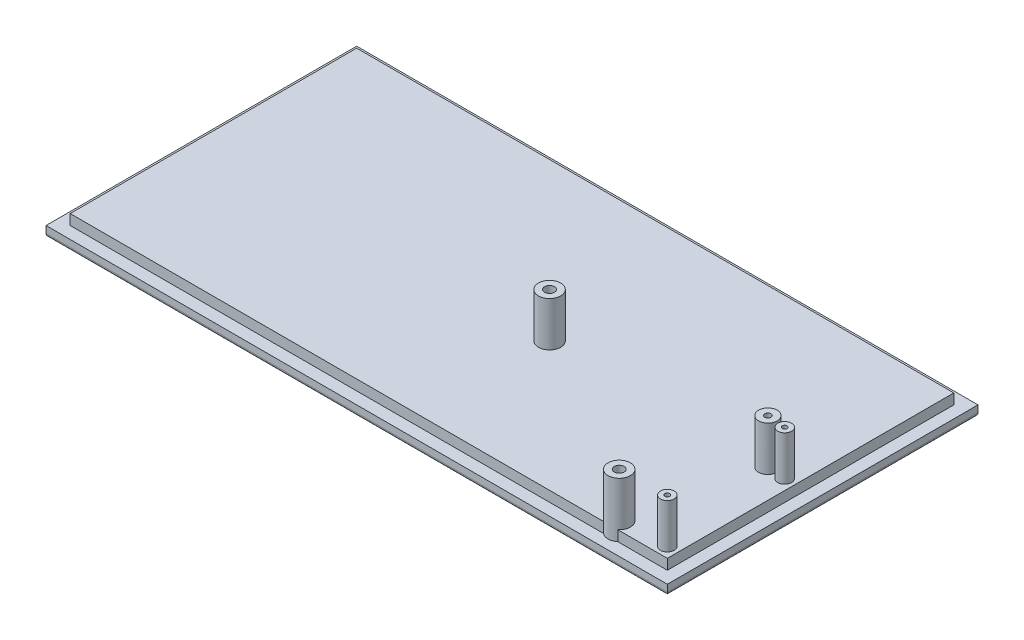
SolidWorks part; units mm, degrees
ref_plane "前视基准面" through (0, 0, 0) normal (0, 0, 1) x (1, 0, 0)
ref_plane "上视基准面" through (0, 0, 0) normal (0, 1, 0) x (1, 0, 0)
ref_plane "右视基准面" through (0, 0, 0) normal (1, 0, 0) x (0, 0, -1)
other "Configuration Table"
sketch "草图1" plane through (0, 0, 0) normal (0, 1, 0) x (1, 0, 0)
  line L1 (-90, 45) -> (90, 45)
  line L2 (-90, 45) -> (-90, -45)
  line L3 (-90, -45) -> (90, -45)
  line L4 (90, 45) -> (90, -45)
  point P7 (25.1581, 37.3018)
  dimension "D1" = 90
  dimension "D2" = 45
  dimension "D3" = 180
  dimension "D4" = 90
extrude "凸台-拉伸1" add sketch "草图1" along normal blind 3
fillet "圆角1" radius 1 4 edges at (0, 0, 45) (90, 0, 0) (0, 0, -45) (-90, 0, 0)
ref_plane "基准面1" through (0, 3, 0) normal (0, 1, 0) x (1, 0, 0)
sketch "草图2" plane through (0, 3, 0) normal (0, 1, 0) x (1, 0, 0)
  line L14 (86.5, -41.5) -> (86.5, 41.5)
  line L15 (-86.5, -41.5) -> (86.5, -41.5)
  line L16 (-86.5, 41.5) -> (-86.5, -41.5)
  line L17 (86.5, 41.5) -> (-86.5, 41.5)
  line L18 (86.5, -41.5) -> (86.5, 41.5)
  line L19 (-86.5, -41.5) -> (86.5, -41.5)
  line L20 (-86.5, 41.5) -> (-86.5, -41.5)
  line L21 (86.5, 41.5) -> (-86.5, 41.5)
  dimension "D1" = 3.5
extrude "凸台-拉伸2" add sketch "草图2" along normal blind 3
sketch "草图3" plane through (0, 3, 0) normal (0, 1, 0) x (1, 0, 0)
  circle A0 centre (14.882, -4.005) radius 1.725 construction
  circle A1 centre (70.082, -39.015) radius 1.725 construction
  circle A2 centre (83.5, -38.5) radius 1 construction
  circle A3 centre (83.5, -4.5) radius 1 construction
  circle A4 centre (78.142, -4.005) radius 1.195 construction
  circle A5 centre (14.882, -4.005) radius 1.725
  circle A6 centre (70.082, -39.015) radius 1.725
  circle A7 centre (83.5, -38.5) radius 1
  circle A8 centre (83.5, -4.5) radius 1
  circle A9 centre (78.142, -4.005) radius 1.195
sketch "草图5" plane through (0, 3, 0) normal (0, 1, 0) x (1, 0, 0)
  circle A5 centre (78.142, -4.005) radius 2.695
  circle A6 centre (78.142, -4.005) radius 2.695
  circle A8 centre (83.5, -4.5) radius 2
  circle A9 centre (83.5, -4.5) radius 2
  circle A11 centre (83.5, -38.5) radius 2
  circle A12 centre (83.5, -38.5) radius 2
  circle A14 centre (14.882, -4.005) radius 3.225
  circle A15 centre (14.882, -4.005) radius 3.225
  circle A17 centre (70.082, -39.015) radius 3.225
  circle A18 centre (70.082, -39.015) radius 3.225
  circle A20 centre (78.142, -4.005) radius 0.895
  circle A21 centre (78.142, -4.005) radius 0.895
  circle A23 centre (83.5, -4.5) radius 0.7
  circle A24 centre (83.5, -4.5) radius 0.7
  circle A26 centre (83.5, -38.5) radius 0.7
  circle A27 centre (83.5, -38.5) radius 0.7
  circle A29 centre (70.082, -39.015) radius 1.425
  circle A30 centre (70.082, -39.015) radius 1.425
  circle A32 centre (14.882, -4.005) radius 1.425
  circle A33 centre (14.882, -4.005) radius 1.425
  dimension "D9" = 0.3
  dimension "D1" = 1.5
  dimension "D2" = 1
  dimension "D3" = 1
  dimension "D4" = 1.5
  dimension "D5" = 1.5
  dimension "D6" = 0.3
  dimension "D7" = 0.3
  dimension "D8" = 0.3
  dimension "D10" = 0.3
extrude "凸台-拉伸3" add sketch "草图5" along normal up to surface (15.9 mm away)
